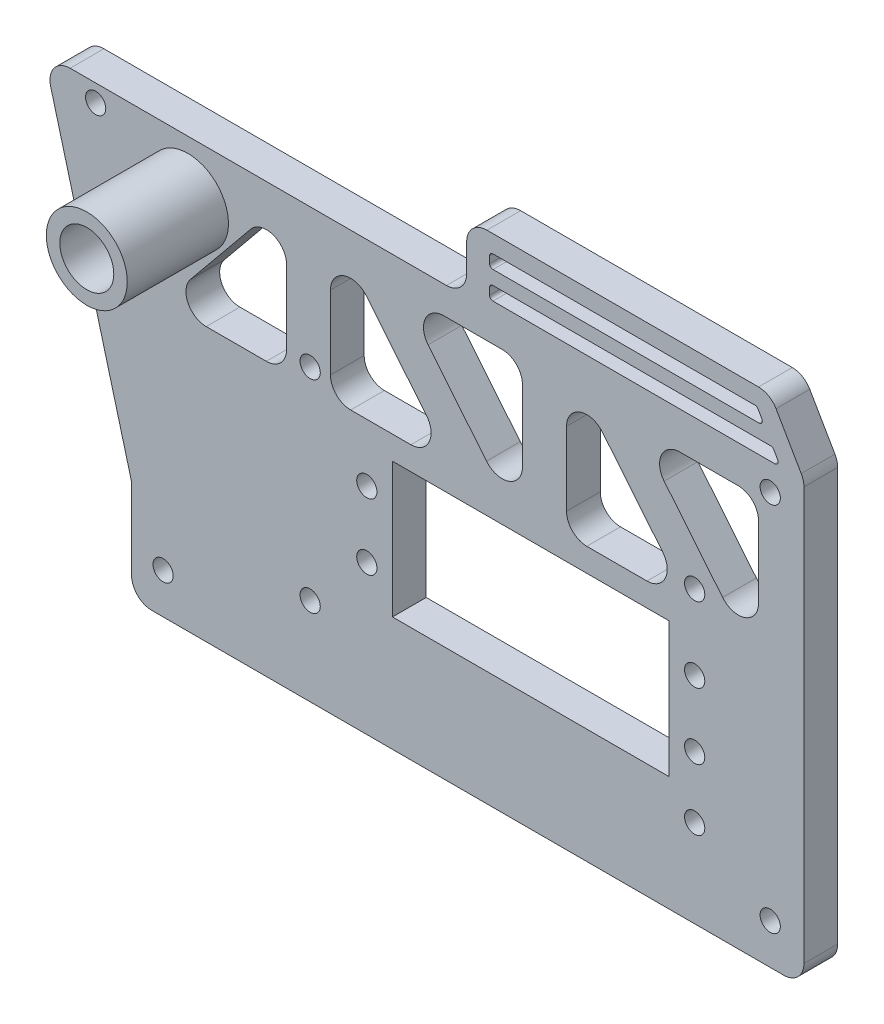
SolidWorks part; units mm, degrees
ref_plane "前视基准面" through (0, 0, 0) normal (0, 0, 1) x (1, 0, 0)
ref_plane "上视基准面" through (0, 0, 0) normal (0, 1, 0) x (1, 0, 0)
ref_plane "右视基准面" through (0, 0, 0) normal (1, 0, 0) x (0, 0, -1)
sketch "草图1" plane through (0, 0, 0) normal (0, 0, 1) x (1, 0, 0)
  line L0 (9.9753, -26.4766) -> (9.9753, 16.164) construction
  line L2 (50.4753, 32.1122) -> (50.4753, -29.084)
  line L3 (47.4753, -32.084) -> (-46.1994, -32.084)
  line L4 (-49.1994, -17.4789) -> (-49.1994, -29.084)
  line L5 (50.4753, 32.916) -> (-49.1994, -32.084) construction
  line L6 (50.4753, -32.084) -> (-49.5143, 31.4731) construction
  line L7 (30.4753, 4.916) -> (-10.5247, 4.916)
  line L8 (30.4753, 4.916) -> (30.4753, -15.084)
  line L9 (30.4753, -15.084) -> (-10.5247, -15.084)
  line L10 (-10.5247, 4.916) -> (-10.5247, -15.084)
  line L11 (30.4753, 4.916) -> (-10.5247, -15.084) construction
  line L12 (30.4753, -15.084) -> (-10.5247, 4.916) construction
  line L13 (34.2753, 10.916) -> (34.2753, -18.8676) construction
  line L14 (47.4759, -5.084) -> (-17.836, -5.084) construction
  line L15 (50.0734, 33.6122) -> (46.3413, 40.0763)
  line L16 (-49.3016, -16.7025) -> (-61.1984, 27.6966)
  line L17 (43.7433, 41.5763) -> (3.4753, 41.5763)
  line L18 (0.4753, 38.5763) -> (0.4753, 34.4731)
  line L19 (-2.5247, 31.4731) -> (-58.3006, 31.4731)
  line L20 (43.7433, 24.3889) -> (43.7433, 13.7931)
  line L21 (38.4214, 11.8934) -> (29.7521, 22.4892)
  line L22 (32.074, 27.3889) -> (40.7433, 27.3889)
  line L26 (27.2056, 8.3889) -> (18.2829, 8.3889)
  line L27 (29.5275, 13.2886) -> (20.6048, 24.1942)
  line L28 (15.2829, 11.3889) -> (15.2829, 22.2945)
  line L32 (-2.926, 27.3889) -> (5.7433, 27.3889)
  line L33 (8.7433, 24.3889) -> (8.7433, 13.7931)
  line L34 (3.4214, 11.8934) -> (-5.2479, 22.4892)
  line L36 (-7.7944, 8.3889) -> (-16.7171, 8.3889)
  line L37 (-5.4725, 13.2886) -> (-14.3952, 24.1942)
  line L50 (-72.926, 27.3889) -> (-64.2567, 27.3889) [skipped]
  line L51 (-66.5786, 11.8934) -> (-75.2479, 22.4892) [skipped]
  line L52 (-89.7171, 11.3889) -> (-89.7171, 22.2945) [skipped]
  line L53 (-77.7944, 8.3889) -> (-86.7171, 8.3889) [skipped]
  line L54 (-75.4725, 13.2886) -> (-84.3952, 24.1942) [skipped]
  line L55 (-61.2567, 24.3889) -> (-61.2567, 13.7931) [skipped]
  line L56 (-31.5786, 11.8934) -> (-40.2479, 22.4892) [skipped]
  line L57 (-26.2567, 24.3889) -> (-26.2567, 13.7931) [skipped]
  line L58 (-37.926, 27.3889) -> (-29.2567, 27.3889) [skipped]
  line L59 (-40.4725, 13.2886) -> (-49.3952, 24.1942) [skipped]
  line L60 (-42.7944, 8.3889) -> (-51.7171, 8.3889) [skipped]
  line L61 (-54.7171, 11.3889) -> (-54.7171, 22.2945) [skipped]
  line L62 (-22.9671, 37.1735) -> (-22.9671, -3.2842) construction
  line L64 (-38.1398, 8.3889) -> (-29.2171, 8.3889)
  line L65 (-40.4617, 13.2886) -> (-31.539, 24.1942)
  line L70 (43.6567, 38.7263) -> (44.234, 37.7263)
  line L72 (3.8772, 38.4763) -> (3.8772, 37.4763)
  line L75 (45.5678, 34.916) -> (4.3772, 34.916)
  line L76 (3.8772, 34.416) -> (3.8772, 33.416)
  line L77 (4.3772, 32.916) -> (46.1452, 32.916)
  line L78 (46.0009, 34.666) -> (46.5782, 33.666)
  line L79 (43.2237, 38.9763) -> (4.3772, 38.9763)
  line L80 (43.801, 36.9763) -> (4.3772, 36.9763)
  line L81 (45.4753, -35.1949) -> (45.4753, 65.7469) construction
  line L82 (58.2283, -26.084) -> (-68.4601, -26.084) construction
  line L83 (45.4753, 28.916) -> (-107.4561, 28.916) construction
  line L84 (40.3368, 10.916) -> (-58.6948, 10.916) construction
  line L85 (-19.7171, 11.3889) -> (-19.7171, 22.2945) [skipped]
  line L86 (-19.7171, 11.3889) -> (-19.7171, 22.2945)
  line L87 (-26.2171, 11.3889) -> (-26.2171, 22.2945)
  line L88 (-22.7247, 10.916) -> (-22.7247, -23.512) construction
  circle A0 centre (34.2753, -0.184) radius 1.5
  circle A2 centre (34.2753, -9.984) radius 1.5
  circle A3 centre (-14.3247, -9.984) radius 1.5
  circle A4 centre (-14.3247, -0.184) radius 1.5
  arc A5 (-46.1994, -32.084) -> (-49.1994, -29.084) centre (-46.1994, -29.084) cw
  arc A6 (50.4753, -29.084) -> (47.4753, -32.084) centre (47.4753, -29.084) cw
  arc A7 (50.0734, 33.6122) -> (50.4753, 32.1122) centre (47.4753, 32.1122) cw
  arc A8 (46.3413, 40.0763) -> (43.7433, 41.5763) centre (43.7433, 38.5763) ccw
  arc A9 (-49.3016, -16.7025) -> (-49.1994, -17.4789) centre (-52.1994, -17.4789) cw
  arc A10 (-58.3006, 31.4731) -> (-61.1984, 27.6966) centre (-58.3006, 28.4731) ccw
  arc A11 (0.4753, 34.4731) -> (-2.5247, 31.4731) centre (-2.5247, 34.4731) cw
  arc A12 (3.4753, 41.5763) -> (0.4753, 38.5763) centre (3.4753, 38.5763) ccw
  arc A13 (15.2829, 22.2945) -> (20.6048, 24.1942) centre (18.2829, 22.2945) cw
  arc A14 (18.2829, 8.3889) -> (15.2829, 11.3889) centre (18.2829, 11.3889) cw
  arc A15 (27.2056, 8.3889) -> (29.5275, 13.2886) centre (27.2056, 11.3889) ccw
  arc A16 (43.7433, 13.7931) -> (38.4214, 11.8934) centre (40.7433, 13.7931) cw
  arc A17 (29.7521, 22.4892) -> (32.074, 27.3889) centre (32.074, 24.3889) cw
  arc A18 (43.7433, 24.3889) -> (40.7433, 27.3889) centre (40.7433, 24.3889) ccw
  arc A22 (8.7433, 24.3889) -> (5.7433, 27.3889) centre (5.7433, 24.3889) ccw
  arc A23 (8.7433, 13.7931) -> (3.4214, 11.8934) centre (5.7433, 13.7931) cw
  arc A24 (-5.2479, 22.4892) -> (-2.926, 27.3889) centre (-2.926, 24.3889) cw
  arc A25 (-19.7171, 22.2945) -> (-14.3952, 24.1942) centre (-16.7171, 22.2945) cw
  arc A26 (-16.7171, 8.3889) -> (-19.7171, 11.3889) centre (-16.7171, 11.3889) cw
  arc A27 (-7.7944, 8.3889) -> (-5.4725, 13.2886) centre (-7.7944, 11.3889) ccw
  arc A40 (-61.2567, 13.7931) -> (-66.5786, 11.8934) centre (-64.2567, 13.7931) cw [skipped]
  arc A41 (-75.2479, 22.4892) -> (-72.926, 27.3889) centre (-72.926, 24.3889) cw [skipped]
  arc A42 (-89.7171, 22.2945) -> (-84.3952, 24.1942) centre (-86.7171, 22.2945) cw [skipped]
  arc A43 (-86.7171, 8.3889) -> (-89.7171, 11.3889) centre (-86.7171, 11.3889) cw [skipped]
  arc A44 (-77.7944, 8.3889) -> (-75.4725, 13.2886) centre (-77.7944, 11.3889) ccw [skipped]
  arc A45 (-61.2567, 24.3889) -> (-64.2567, 27.3889) centre (-64.2567, 24.3889) ccw [skipped]
  arc A46 (-26.2567, 13.7931) -> (-31.5786, 11.8934) centre (-29.2567, 13.7931) cw [skipped]
  arc A47 (-40.2479, 22.4892) -> (-37.926, 27.3889) centre (-37.926, 24.3889) cw [skipped]
  arc A48 (-26.2567, 24.3889) -> (-29.2567, 27.3889) centre (-29.2567, 24.3889) ccw [skipped]
  arc A49 (-42.7944, 8.3889) -> (-40.4725, 13.2886) centre (-42.7944, 11.3889) ccw [skipped]
  arc A50 (-54.7171, 22.2945) -> (-49.3952, 24.1942) centre (-51.7171, 22.2945) cw [skipped]
  arc A51 (-51.7171, 8.3889) -> (-54.7171, 11.3889) centre (-51.7171, 11.3889) cw [skipped]
  arc A52 (-29.2171, 8.3889) -> (-26.2171, 11.3889) centre (-29.2171, 11.3889) ccw
  arc A53 (-38.1398, 8.3889) -> (-40.4617, 13.2886) centre (-38.1398, 11.3889) cw
  arc A54 (-26.2171, 22.2945) -> (-31.539, 24.1942) centre (-29.2171, 22.2945) ccw
  arc A55 (4.3772, 38.9763) -> (3.8772, 38.4763) centre (4.3772, 38.4763) ccw
  arc A56 (3.8772, 37.4763) -> (4.3772, 36.9763) centre (4.3772, 37.4763) ccw
  arc A57 (4.3772, 34.916) -> (3.8772, 34.416) centre (4.3772, 34.416) ccw
  arc A58 (3.8772, 33.416) -> (4.3772, 32.916) centre (4.3772, 33.416) ccw
  arc A59 (46.1452, 32.916) -> (46.5782, 33.666) centre (46.1452, 33.416) ccw
  arc A60 (45.5678, 34.916) -> (46.0009, 34.666) centre (45.5678, 34.416) cw
  arc A61 (43.801, 36.9763) -> (44.234, 37.7263) centre (43.801, 37.4763) ccw
  arc A62 (43.2237, 38.9763) -> (43.6567, 38.7263) centre (43.2237, 38.4763) cw
  circle A64 centre (45.4753, -26.084) radius 1.5
  circle A65 centre (45.4753, 28.916) radius 1.5
  circle A66 centre (-44.5247, -26.084) radius 1.5
  circle A68 centre (-54.5247, 28.916) radius 1.5
  circle A69 centre (34.2753, 10.916) radius 1.5
  circle A70 centre (-22.7247, 10.916) radius 1.5
  circle A71 centre (34.2753, -19.084) radius 1.5
  circle A72 centre (-22.7247, -19.084) radius 1.5
  point P0 (0, 0)
  point P6 (9.9753, -5.084)
  point P41 (45.4753, 41.5763)
  point P44 (-49.1994, -17.084)
  point P66 (43.7433, 5.3889)
  point P69 (25.7433, 27.3889)
  point P72 (43.7433, 27.3889)
  point P107 (6.4753, 35.5763)
  point P112 (41.4753, 33.5763)
  point P113 (3.8772, 40.0763)
  point P115 (41.4753, 35.5763)
  point P189 (42.8772, 40.0763)
  dimension "D7" = 3
  dimension "D8" = 3
  dimension "D16" = 3
  dimension "D21" = 3
  dimension "D27" = 2.6
  dimension "D28" = 0.5
  dimension "D29" = 3
  dimension "D32" = 3
  dimension "D34" = 3
  dimension "D36" = 3
  dimension "D38" = 3
  dimension "D40" = 3
  dimension "D23" = 3
  dimension "D42" = 3
  dimension "D1" = 100
  dimension "D2" = 65
  dimension "D3" = 41
  dimension "D4" = 20
  dimension "D5" = 20
  dimension "D6" = 17
  dimension "D9" = 9.8
  dimension "D10" = 4.9
  dimension "D11" = 24.3
  dimension "D12" = 10
  dimension "D13" = 50
  dimension "D14" = 15
  dimension "D15" = 15
  dimension "D17" = 22
  dimension "D18" = 2
  dimension "D19" = 3
  dimension "D20" = 6
  dimension "D24" = 3
  dimension "D25" = 39
  dimension "D26" = 2
  dimension "D30" = 5
  dimension "D31" = 6
  dimension "D33" = 55
  dimension "D35" = 90
  dimension "D37" = 100
  dimension "D39" = 6
  dimension "D41" = 57
  dimension "D43" = 30
  dimension "D44" = 30
  dimension "D45" = 0
  dimension "D22" = 4
extrude "凸台-拉伸1" add sketch "草图1" along normal blind 5
sketch "草图6" plane through (0, 0, 5) normal (0, 0, 1) x (1, 0, 0)
  circle A0 centre (-40.8367, 23.2673) radius 6
  circle A1 centre (-40.8367, 23.2673) radius 4
  dimension "D2" = 12
  dimension "D3" = 8
  dimension "D1" = 47
extrude "凸台-拉伸3" add sketch "草图6" along normal blind 15
sketch "草图7" plane through (0, 0, 5) normal (0, 0, 1) x (1, 0, 0)
  circle A0 centre (-40.8367, 23.2673) radius 2.5
  dimension "D1" = 5
extrude "切除-拉伸1" cut sketch "草图7" against normal through all
